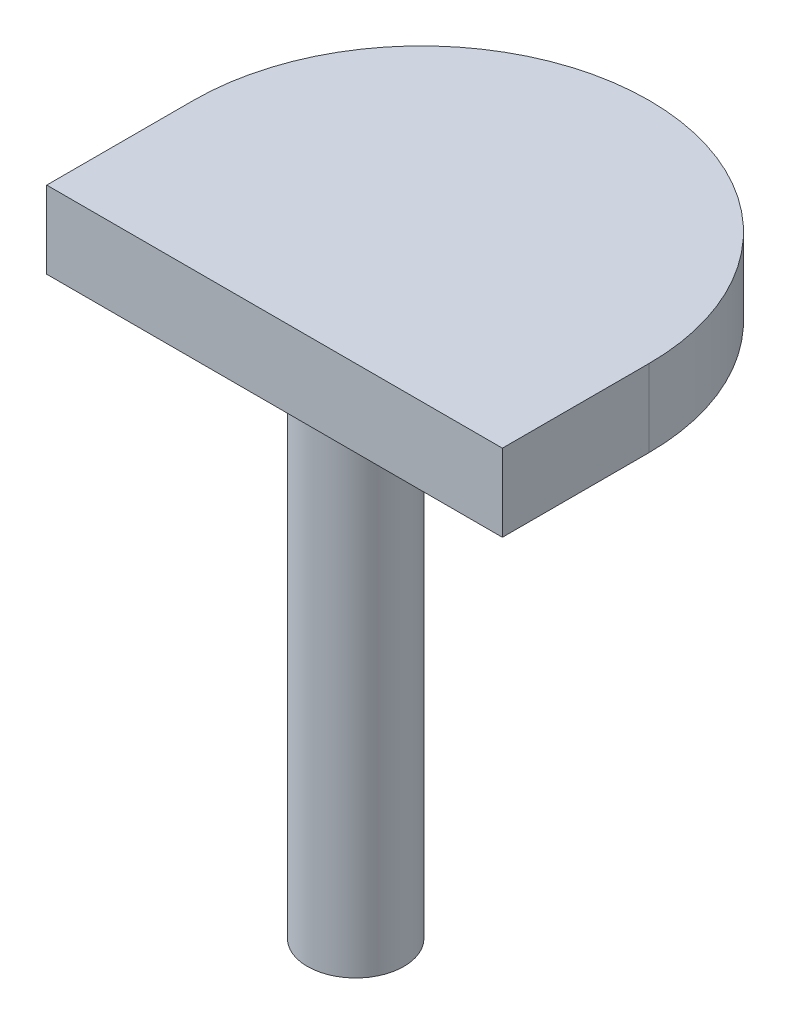
SolidWorks part; units mm, degrees
ref_plane "前视基准面" through (0, 0, 0) normal (0, 0, 1) x (1, 0, 0)
ref_plane "上视基准面" through (0, 0, 0) normal (0, 1, 0) x (1, 0, 0)
ref_plane "右视基准面" through (0, 0, 0) normal (1, 0, 0) x (0, 0, -1)
other "Configuration Table"
sketch "Sketch1" plane through (0, 0, 0) normal (0, 1, 0) x (1, 0, 0)
  circle A0 centre (0, 0) radius 1.25
  dimension "D1" = 2.5
extrude "Boss-Extrude1" add sketch "Sketch1" along normal blind 14
sketch "Sketch3" plane through (0, 14, 0) normal (0, 1, 0) x (1, 0, 0)
  line L0 (5.9, -2.1) -> (-5.9, -2.1)
  line L1 (6, -2.2) -> (-6, -2.2) construction
  line L2 (6, -2.2) -> (6, 1.8) construction
  line L3 (6, 1.8) -> (-6, 1.8) construction
  line L4 (-6, -2.2) -> (-6, 1.8) construction
  line L5 (-5.9, -2.1) -> (-5.9, 1.7)
  line L6 (5.9, 1.7) -> (-5.9, 1.7)
  line L7 (5.9, -2.1) -> (5.9, 1.7)
  dimension "D1" = 2.2
  dimension "D2" = 1.8
  dimension "D3" = 6
  dimension "D4" = 12
  dimension "D5" = 0.1
extrude "Boss-Extrude2" add sketch "Sketch3" along normal blind 1 and the other way blind 1
sketch "Sketch4" plane through (0, 15, 0) normal (0, 1, 0) x (1, 0, 0)
  line L0 (5.9, 1.7) -> (-5.9, 1.7) construction
  line L1 (5.9, -2.1) -> (5.9, 1.7) construction
  line L2 (-5.9, 1.7) -> (-5.9, -2.1) construction
  line L3 (5.9, 1.7) -> (-5.9, 1.7)
  arc A0 (5.9, 1.7) -> (-5.9, 1.7) centre (0, 1.7) ccw
extrude "Boss-Extrude3" add sketch "Sketch4" against normal blind 2
